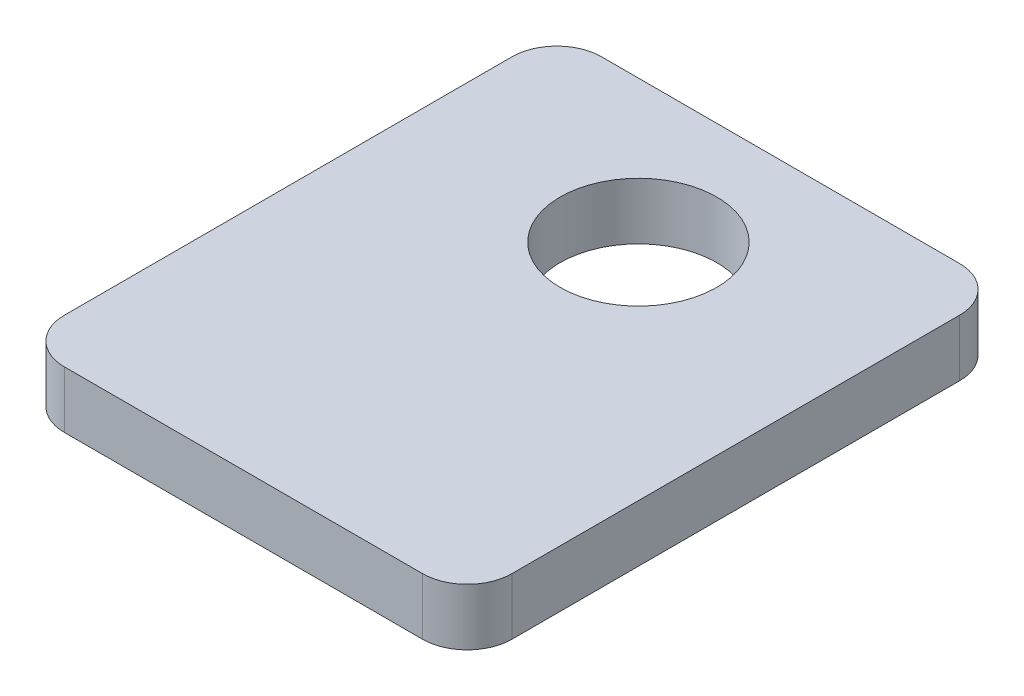
SolidWorks part; units mm, degrees
material "Copper"
ref_plane "Front Plane" through (0, 0, 0) normal (0, 0, 1) x (1, 0, 0)
ref_plane "Top Plane" through (0, 0, 0) normal (0, 1, 0) x (1, 0, 0)
ref_plane "Right Plane" through (0, 0, 0) normal (1, 0, 0) x (0, 0, -1)
sketch "Sketch1" plane through (0, 0, 0) normal (0, 1, 0) x (1, 0, 0)
  line L1 (0, 0) -> (10, 0)
  line L2 (0, 0) -> (0, -12)
  line L3 (0, -12) -> (10, -12)
  line L4 (10, 0) -> (10, -12)
  circle A0 centre (5, -3.175) radius 1.75
  point P8 (5, 0)
  dimension "D2" = 3.5
  dimension "D1" = 10
  dimension "D3" = 3.175
  dimension "D4" = 12
extrude "Boss-Extrude1" add sketch "Sketch1" along normal blind 1.27
fillet "Fillet1" radius 1 4 edges at (0, 0.635, 0) (0, 0.635, 12) (10, 0.635, 12) (10, 0.635, 0)
